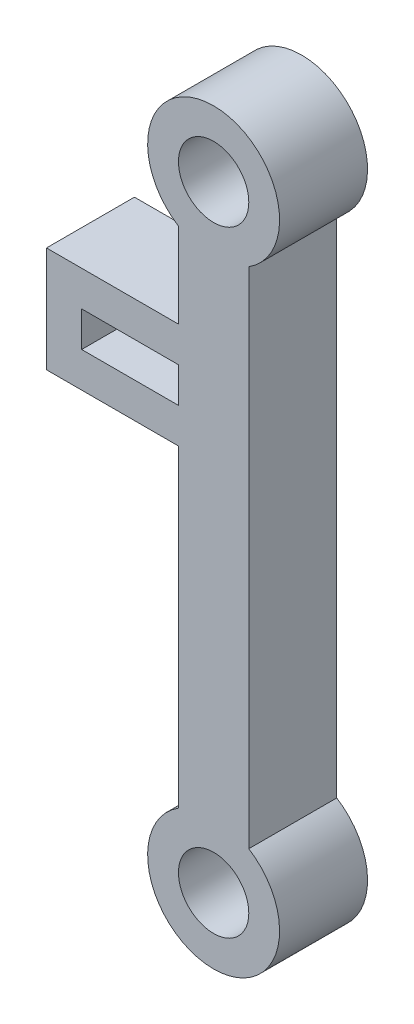
SolidWorks part; units mm, degrees
material "ABS"
ref_plane "Plano frontal" through (0, 0, 0) normal (0, 0, 1) x (1, 0, 0)
ref_plane "Plano superior" through (0, 0, 0) normal (0, 1, 0) x (1, 0, 0)
ref_plane "Plano direito" through (0, 0, 0) normal (1, 0, 0) x (0, 0, -1)
sketch "Esboço1" plane through (0, 0, 0) normal (0, 0, 1) x (1, 0, 0)
  line L0 (4, 63.6557) -> (4, 6.3443)
  line L1 (0, 70) -> (0, 0) construction
  line L2 (-4, 63.6557) -> (-4, 54)
  line L3 (-4, 42) -> (-19, 42)
  line L4 (-19, 42) -> (-19, 54)
  line L5 (-19, 54) -> (-4, 54)
  line L7 (-4, 42) -> (-4, 6.3443)
  line L8 (-15, 50) -> (-4, 50)
  line L9 (-15, 50) -> (-15, 46)
  line L10 (-15, 46) -> (-4, 46)
  line L11 (-4, 50) -> (-4, 46)
  line L12 (-15, 50) -> (-4, 46) construction
  line L13 (-15, 46) -> (-4, 50) construction
  circle A0 centre (0, 70) radius 4
  circle A1 centre (0, 0) radius 4
  arc A2 (4, 63.6557) -> (-4, 63.6557) centre (0, 70) ccw
  arc A3 (-4, 6.3443) -> (4, 6.3443) centre (0, 0) ccw
  point P14 (-9.5, 48)
  point P19 (-24.5979, 19.7123)
  point P20 (0, 0)
  point P21 (-19, 48)
  dimension "D1" = 8
  dimension "D2" = 15
  dimension "D3" = 70
  dimension "D4" = 8
  dimension "D5" = 16
  dimension "D6" = 12
  dimension "D7" = 15
  dimension "D8" = 4
  dimension "D9" = 4
extrude "Ressalto-extrusão1" add sketch "Esboço1" along normal blind 10 contours L0 A3 L2 A2
